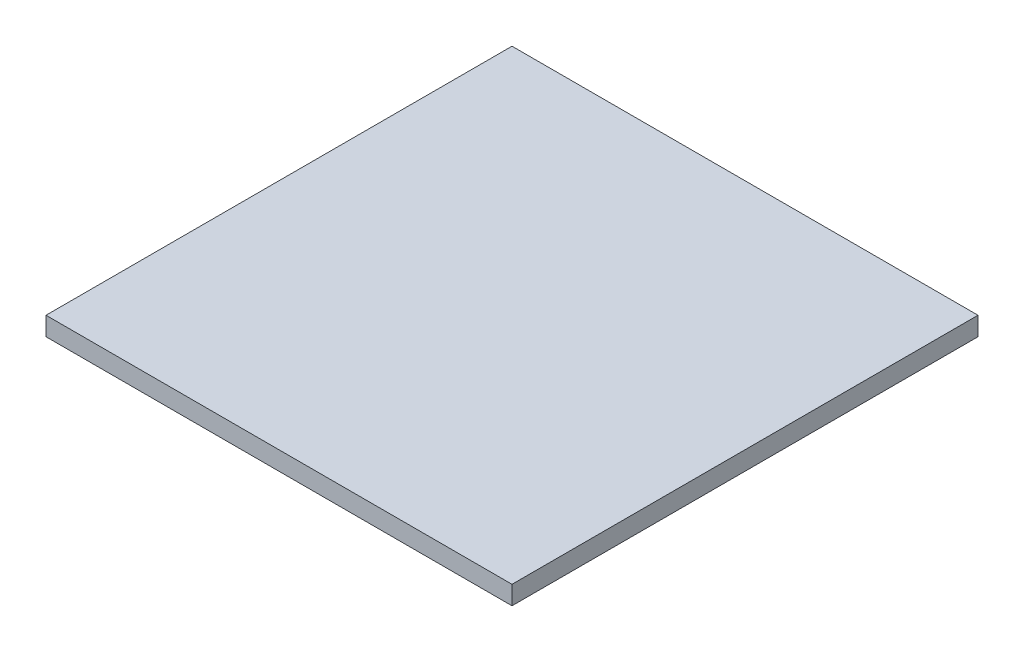
SolidWorks part; units mm, degrees
ref_plane "Front Plane" through (0, 0, 0) normal (0, 0, 1) x (1, 0, 0)
ref_plane "Top Plane" through (0, 0, 0) normal (0, 1, 0) x (1, 0, 0)
ref_plane "Right Plane" through (0, 0, 0) normal (1, 0, 0) x (0, 0, -1)
sketch "Sketch1" plane through (0, 0, 0) normal (0, 1, 0) x (1, 0, 0)
  line L0 (0, 250) -> (0, -250)
  line L1 (-250, -250) -> (250, -250)
  line L2 (-250, -250) -> (-250, 250)
  line L3 (-250, 250) -> (250, 250)
  line L4 (250, -250) -> (250, 250)
  line L5 (-250, -250) -> (250, 250) construction
  line L6 (-250, 250) -> (250, -250) construction
  line L8 (-250, 0) -> (250, 0)
  point P0 (0, 0)
  dimension "D1" = 500
  dimension "D2" = 500
extrude "Boss-Extrude1" add sketch "Sketch1" along normal blind 20 contours L2 L3 L4 L1
